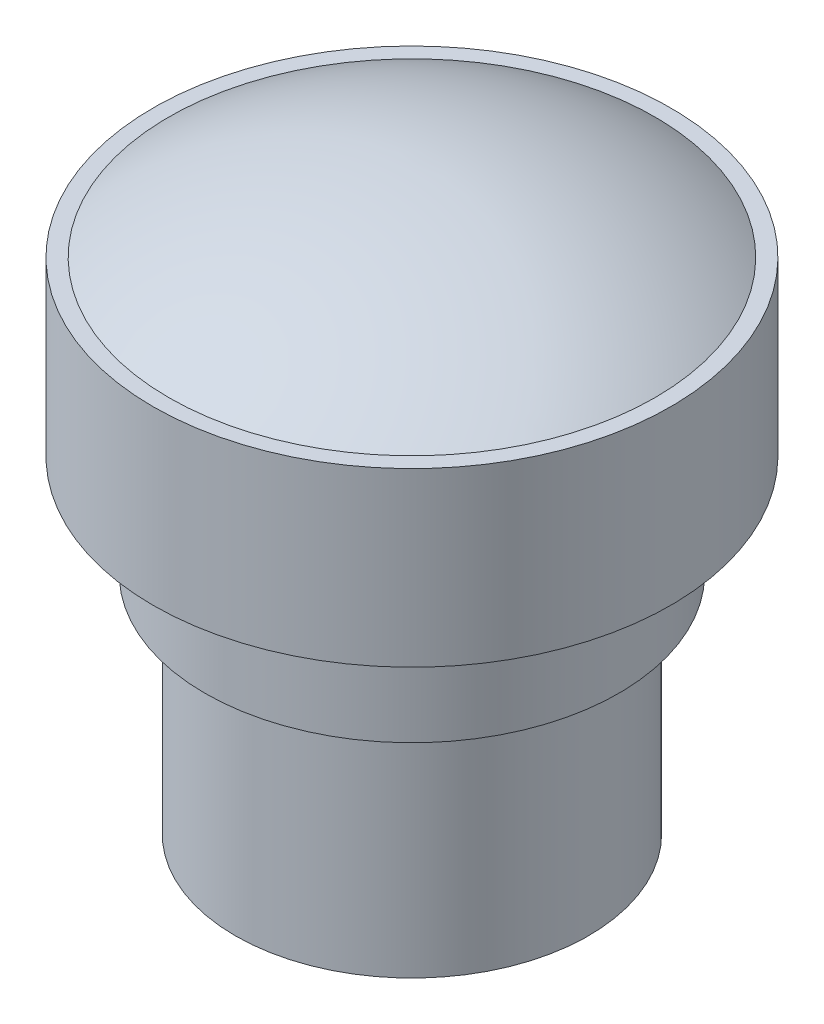
SolidWorks part; units mm, degrees
ref_plane "前视基准面" through (0, 0, 0) normal (0, 0, 1) x (1, 0, 0)
ref_plane "上视基准面" through (0, 0, 0) normal (0, 1, 0) x (1, 0, 0)
ref_plane "右视基准面" through (0, 0, 0) normal (1, 0, 0) x (0, 0, -1)
sketch "草图1" plane through (0, 0, 0) normal (0, 0, 1) x (1, 0, 0)
  line L0 (0, 0) -> (5.8, 0)
  line L1 (5.8, 0) -> (5.8, 7.4)
  line L2 (5.8, 7.4) -> (6.8, 7.4)
  line L3 (6.8, 7.4) -> (6.8, 10.75)
  line L4 (6.8, 10.75) -> (8.5, 10.75)
  line L5 (8.5, 10.75) -> (8.5, 16.4)
  line L6 (8.5, 16.4) -> (7.9844, 16.4)
  line L7 (0, 4.9) -> (0, 0) construction
  line L8 (0, 0) -> (0, 18.93) construction
  line L15 (0, 18.9) -> (0, 0)
  arc A0 (7.9844, 16.4) -> (0, 18.9) centre (0, 4.9) ccw
  dimension "D7" = 14
  dimension "D8" = 4.9
  dimension "D1" = 5.8
  dimension "D2" = 7.4
  dimension "D3" = 6.8
  dimension "D4" = 8.5
  dimension "D5" = 10.75
  dimension "D6" = 16.4
revolve "旋转1" add sketch "草图1" angle 360 about L15
